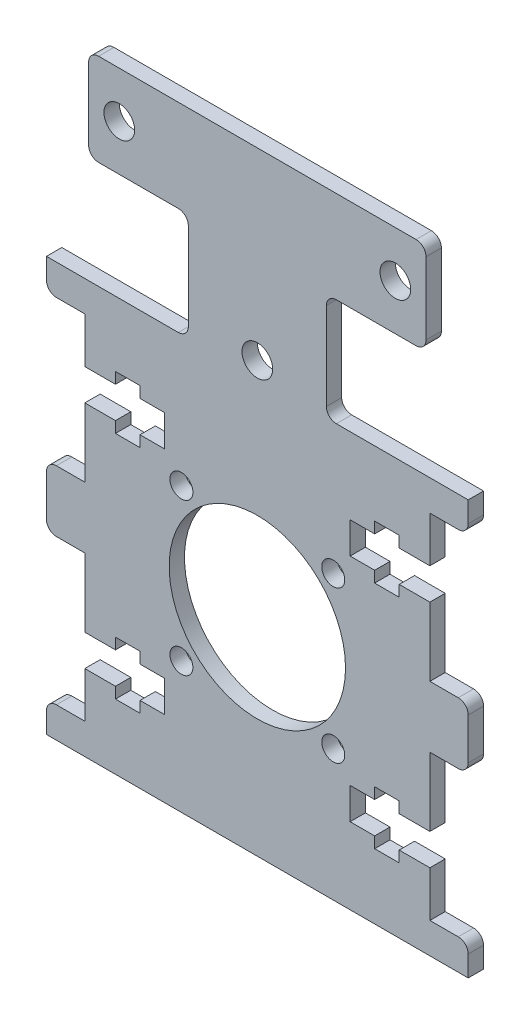
SolidWorks part; units mm, degrees
ref_plane "前视基准面" through (0, 0, 0) normal (0, 0, 1) x (1, 0, 0)
ref_plane "上视基准面" through (0, 0, 0) normal (0, 1, 0) x (1, 0, 0)
ref_plane "右视基准面" through (0, 0, 0) normal (1, 0, 0) x (0, 0, -1)
sketch "草图1" plane through (0, 0, 0) normal (0, 0, 1) x (1, 0, 0)
  line L0 (-22.5, 0) -> (-24.9483, 0) construction
  line L1 (22.5, -27) -> (-22.5, -27)
  line L3 (22.5, 27) -> (-22.5, 27) construction
  line L4 (-22.5, -27) -> (-22.5, 27) construction
  line L5 (22.5, -27) -> (-22.5, 27) construction
  line L6 (22.5, 27) -> (-22.5, -27) construction
  line L7 (-22.5, 4) -> (-27.5, 4)
  line L8 (-27.5, 4) -> (-27.5, -4)
  line L9 (-27.5, -4) -> (-22.5, -4)
  line L10 (-22.5, 17.05) -> (-18.5, 17.05)
  line L11 (-18.5, 17.05) -> (-18.5, 18.5)
  line L12 (-18.5, 18.5) -> (-15.3, 18.5)
  line L13 (-15.3, 18.5) -> (-15.3, 17.05)
  line L14 (-15.3, 17.05) -> (-12.1, 17.05)
  line L15 (-12.1, 17.05) -> (-12.1, 12.95)
  line L16 (-12.1, 12.95) -> (-15.3, 12.95)
  line L17 (-15.3, 12.95) -> (-15.3, 11.5)
  line L18 (-15.3, 11.5) -> (-18.5, 11.5)
  line L19 (-18.5, 11.5) -> (-18.5, 12.95)
  line L20 (-18.5, 12.95) -> (-22.5, 12.95)
  line L21 (-18.5, -12.95) -> (-22.5, -12.95)
  line L22 (-18.5, -11.5) -> (-18.5, -12.95)
  line L23 (-15.3, -11.5) -> (-18.5, -11.5)
  line L24 (-15.3, -12.95) -> (-15.3, -11.5)
  line L25 (-12.1, -12.95) -> (-15.3, -12.95)
  line L26 (-12.1, -17.05) -> (-12.1, -12.95)
  line L27 (-15.3, -17.05) -> (-12.1, -17.05)
  line L28 (-15.3, -18.5) -> (-15.3, -17.05)
  line L29 (-18.5, -18.5) -> (-15.3, -18.5)
  line L30 (-18.5, -17.05) -> (-18.5, -18.5)
  line L31 (-22.5, -17.05) -> (-18.5, -17.05)
  line L32 (-22.5, -23) -> (-27.5, -23)
  line L33 (-27.5, -23) -> (-27.5, -27)
  line L34 (-27.5, -27) -> (-22.5, -27)
  line L35 (-27.5, 23) -> (-27.5, 27)
  line L36 (-22.5, 23) -> (-27.5, 23)
  line L37 (-27.5, 27) -> (-22.5, 27)
  line L38 (0, 0) -> (0, -4) construction
  line L39 (22.5, -27) -> (22.5, 27) construction
  line L40 (22.5, 0) -> (24.9483, 0) construction
  line L41 (27.5, 27) -> (22.5, 27)
  line L42 (22.5, 23) -> (27.5, 23)
  line L43 (27.5, 23) -> (27.5, 27)
  line L44 (27.5, -27) -> (22.5, -27)
  line L45 (27.5, -23) -> (27.5, -27)
  line L46 (22.5, -23) -> (27.5, -23)
  line L47 (22.5, -17.05) -> (18.5, -17.05)
  line L48 (18.5, -17.05) -> (18.5, -18.5)
  line L49 (18.5, -18.5) -> (15.3, -18.5)
  line L50 (15.3, -18.5) -> (15.3, -17.05)
  line L51 (15.3, -17.05) -> (12.1, -17.05)
  line L52 (12.1, -17.05) -> (12.1, -12.95)
  line L53 (12.1, -12.95) -> (15.3, -12.95)
  line L54 (15.3, -12.95) -> (15.3, -11.5)
  line L55 (15.3, -11.5) -> (18.5, -11.5)
  line L56 (18.5, -11.5) -> (18.5, -12.95)
  line L57 (18.5, -12.95) -> (22.5, -12.95)
  line L58 (18.5, 12.95) -> (22.5, 12.95)
  line L59 (18.5, 11.5) -> (18.5, 12.95)
  line L60 (15.3, 11.5) -> (18.5, 11.5)
  line L61 (15.3, 12.95) -> (15.3, 11.5)
  line L62 (12.1, 12.95) -> (15.3, 12.95)
  line L63 (12.1, 17.05) -> (12.1, 12.95)
  line L64 (15.3, 17.05) -> (12.1, 17.05)
  line L65 (15.3, 18.5) -> (15.3, 17.05)
  line L66 (18.5, 18.5) -> (15.3, 18.5)
  line L67 (18.5, 17.05) -> (18.5, 18.5)
  line L68 (22.5, 17.05) -> (18.5, 17.05)
  line L69 (27.5, -4) -> (22.5, -4)
  line L70 (27.5, 4) -> (27.5, -4)
  line L71 (22.5, 4) -> (27.5, 4)
  line L72 (-22.5, 23) -> (-22.5, 17.05)
  line L73 (-22.5, 12.95) -> (-22.5, 4)
  line L74 (-22.5, -4) -> (-22.5, -12.95)
  line L75 (-22.5, -17.05) -> (-22.5, -23)
  line L76 (22.5, -23) -> (22.5, -17.05)
  line L77 (22.5, -12.95) -> (22.5, -4)
  line L78 (22.5, 4) -> (22.5, 12.95)
  line L79 (22.5, 23) -> (22.5, 17.05)
  line L80 (0, 0) -> (0, 47) construction
  line L81 (0, 47) -> (-18, 47) construction
  line L82 (22, 53) -> (-22, 53)
  line L83 (-22, 53) -> (-22, 41)
  line L84 (-22, 41) -> (-9, 41)
  line L85 (-9, 41) -> (-9, 27)
  line L86 (-9, 27) -> (-22.5, 27)
  line L87 (22, 53) -> (22, 41)
  line L88 (22, 41) -> (9, 41)
  line L89 (9, 41) -> (9, 27)
  line L90 (9, 27) -> (22.5, 27)
  line L91 (-12.1, 15) -> (-22.5, 15) construction
  circle A0 centre (0, 0) radius 14 construction
  circle A1 centre (9.8995, 9.8995) radius 1.5
  circle A5 centre (0, 0) radius 11.5
  circle A6 centre (9.8995, -9.8995) radius 1.5
  circle A7 centre (-9.8995, -9.8995) radius 1.5
  circle A8 centre (-9.8995, 9.8995) radius 1.5
  circle A9 centre (-18, 47) radius 2
  circle A10 centre (18, 47) radius 2
  circle A11 centre (0, 29) radius 2
  point P35 (-16.9, 11.5)
  point P48 (-21.5, -15)
  point P91 (21.5, -15)
  dimension "D2" = 23
  dimension "D12" = 3
  dimension "D17" = 28
  dimension "D21" = 18
  dimension "D22" = 18
  dimension "D27" = 4
  dimension "D3" = 45
  dimension "D4" = 54
  dimension "D5" = 8
  dimension "D6" = 5
  dimension "D7" = 4
  dimension "D8" = 15
  dimension "D9" = 3.2
  dimension "D10" = 4
  dimension "D11" = 4.1
  dimension "D13" = 7
  dimension "D14" = 4
  dimension "D15" = 5
  dimension "D19" = 29
  dimension "D20" = 18
  dimension "D23" = 13
  dimension "D24" = 12
  dimension "D25" = 6
  dimension "D26" = 4
  dimension "D18" = 4
extrude "凸台-拉伸1" add sketch "草图1" along normal blind 2
sketch "草图2" plane through (-22.5, 0, 0) normal (-1, 0, 0) x (0, 0, 1)
  line L0 (1, 17.05) -> (1, 12.95) construction
  line L1 (2, 17.05) -> (0, 17.05) construction
  line L2 (2, 12.95) -> (0, 12.95) construction
  line L3 (-0.15, 27.15) -> (4.15, 27.15) construction
  line L4 (4.15, -4.15) -> (-0.15, -4.15)
  line L5 (4.15, -4.15) -> (4.15, 4.15)
  line L6 (4.15, 4.15) -> (-0.15, 4.15)
  line L7 (-0.15, -4.15) -> (-0.15, 4.15)
  line L8 (4.15, -4.15) -> (-0.15, 4.15) construction
  line L9 (4.15, 4.15) -> (-0.15, -4.15) construction
  line L18 (4.15, 27.15) -> (4.15, 22.85)
  line L19 (-0.15, 22.85) -> (4.15, 22.85)
  line L20 (-0.15, 27.15) -> (-0.15, 22.85)
  line L21 (2, 0) -> (2.8697, 0) construction
  line L22 (-0.15, -27.15) -> (4.15, -27.15) construction
  line L23 (1, -17.05) -> (1, -12.95) construction
  line L24 (-0.15, -27.15) -> (-0.15, -22.85)
  line L25 (-0.15, -22.85) -> (4.15, -22.85)
  line L26 (4.15, -27.15) -> (4.15, -22.85)
  line L27 (4.15, -27.15) -> (8, -27.15)
  line L28 (8, -27.15) -> (8, 27.15)
  line L29 (8, 27.15) -> (4.15, 27.15)
  line L30 (-0.15, -27.15) -> (-64.002, -27.15)
  line L31 (-64.002, -27.15) -> (-64.002, 27.15)
  line L32 (-64.002, 27.15) -> (-0.15, 27.15)
  circle A0 centre (1, 15) radius 2.05
  circle A1 centre (1, -15) radius 2.05
  point P8 (2, 0)
  dimension "D1" = 8.3
  dimension "D2" = 4.3
sketch "草图3" plane through (22.5, 0, 0) normal (1, 0, 0) x (0, 0, -1)
  line L0 (-1, 12.95) -> (-1, 17.05)
  line L1 (-2, 12.95) -> (0, 12.95) construction
  line L2 (-2, 17.05) -> (0, 17.05) construction
  circle A0 centre (-1, 15) radius 2.05
fillet "圆角1" radius 1.3 16 edges at (-9, 27, 1) (9, 27, 1) (9, 41, 1) (-9, 41, 1) (22, 53, 1) (22, 41, 1) (-22, 53, 1) (-22, 41, 1) (-27.5, -23, 1) (-27.5, 23, 1) (-27.5, 4, 1) (-27.5, -4, 1) (27.5, -23, 1) (27.5, 4, 1) (27.5, -4, 1) (27.5, 23, 1)
